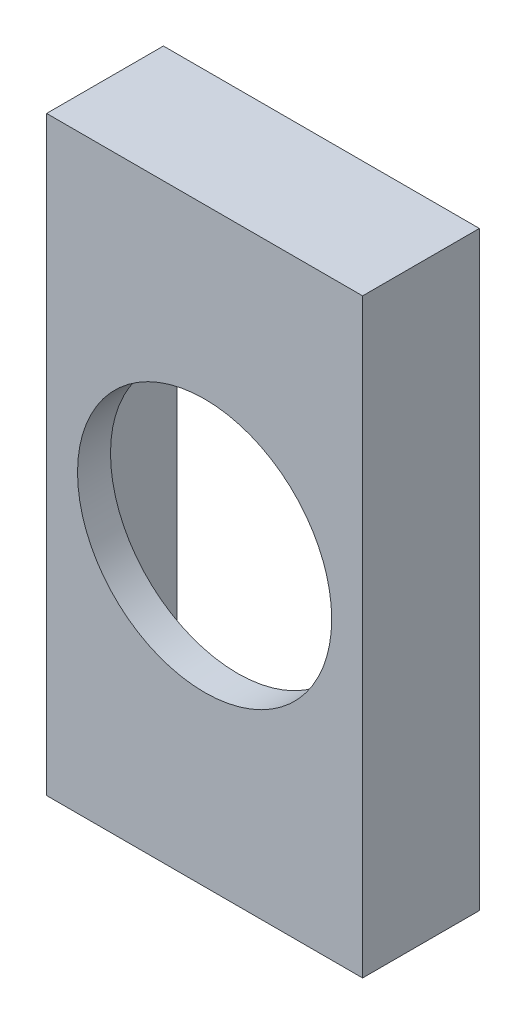
SolidWorks part; units mm, degrees
ref_plane "Plano frontal" through (0, 0, 0) normal (0, 0, 1) x (1, 0, 0)
ref_plane "Plano superior" through (0, 0, 0) normal (0, 1, 0) x (1, 0, 0)
ref_plane "Plano direito" through (0, 0, 0) normal (1, 0, 0) x (0, 0, -1)
sketch "Esboço1" plane through (0, 0, 0) normal (0, 0, 1) x (1, 0, 0)
  line L1 (-11.5, -21.5) -> (11.5, -21.5)
  line L2 (-11.5, -21.5) -> (-11.5, 21.5)
  line L3 (-11.5, 21.5) -> (11.5, 21.5)
  line L4 (11.5, -21.5) -> (11.5, 21.5)
  line L5 (-11.5, -21.5) -> (11.5, 21.5) construction
  line L6 (-11.5, 21.5) -> (11.5, -21.5) construction
  point P0 (0, 0)
  dimension "D1" = 23
  dimension "D2" = 43
extrude "Ressalto-extrusão1" add sketch "Esboço1" along normal blind 8.5
sketch "Esboço2" plane through (0, 0, 0) normal (0, 0, -1) x (-1, 0, 0)
  line L0 (-11.5, 21.5) -> (11.5, 21.5) construction
  line L1 (-10.5, -16.5) -> (10.5, -16.5)
  line L2 (-10.5, -16.5) -> (-10.5, 16.5)
  line L3 (-10.5, 16.5) -> (10.5, 16.5)
  line L4 (10.5, -16.5) -> (10.5, 16.5)
  line L5 (-10.5, -16.5) -> (10.5, 16.5) construction
  line L6 (-10.5, 16.5) -> (10.5, -16.5) construction
  line L7 (-11.5, -21.5) -> (-11.5, 21.5) construction
  point P0 (0, 0)
  dimension "D1" = 5
  dimension "D2" = 1
extrude "Corte-extrusão1" cut sketch "Esboço2" against normal offset from surface (6.1 mm away) 2.4 up to face at (0, 0, 8.5)
sketch "Esboço3" plane through (0, 0, 8.5) normal (0, 0, 1) x (1, 0, 0)
  circle A0 centre (0, 0) radius 9.25
  dimension "D1" = 18.5
extrude "Corte-extrusão2" cut sketch "Esboço3" against normal through all
sketch "Esboço4" plane through (0, 0, 0) normal (0, 0, -1) x (-1, 0, 0)
  line L0 (-11.5, 0) -> (11.5, 0) construction
  line L1 (-11.5, -21.5) -> (-11.5, 21.5) construction
  line L2 (11.5, 21.5) -> (11.5, -21.5) construction
  line L3 (-11.5, 21.5) -> (11.5, 21.5) construction
  circle A0 centre (0, 19) radius 1
  circle A1 centre (0, -19) radius 1
  dimension "D1" = 2
  dimension "D2" = 2.5
extrude "Corte-extrusão3" cut sketch "Esboço4" against normal blind 4
